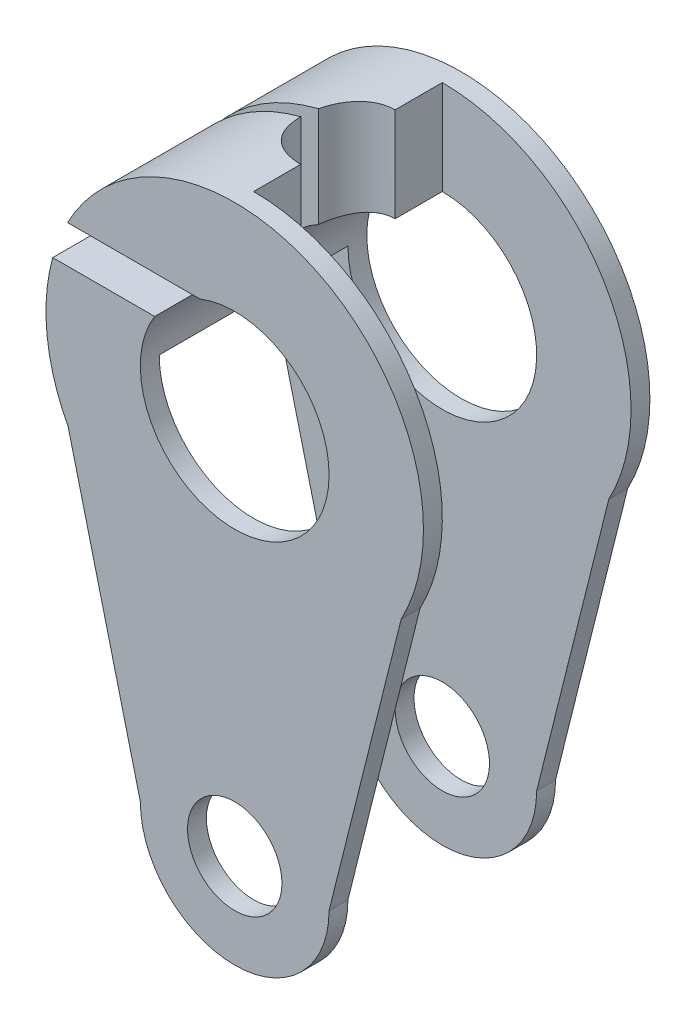
SolidWorks part; units mm, degrees
material "AISI 1020"
ref_plane "Alzado" through (0, 0, 0) normal (0, 0, 1) x (1, 0, 0)
ref_plane "Planta" through (0, 0, 0) normal (0, 1, 0) x (1, 0, 0)
ref_plane "Vista lateral" through (0, 0, 0) normal (1, 0, 0) x (0, 0, -1)
sketch "Croquis1" plane through (0, 0, 0) normal (0, 0, 1) x (1, 0, 0)
  line L0 (0, 0) -> (0, -12.7) construction
  line L1 (-5.6029, -2.9882) -> (-3.175, -12.7)
  line L2 (3.175, -12.7) -> (5.6029, -2.9882)
  arc A0 (5.6029, -2.9882) -> (-5.6029, -2.9882) centre (0, 0) ccw
  arc A1 (-3.175, -12.7) -> (3.175, -12.7) centre (0, -12.7) ccw
  circle A2 centre (0, 0) radius 3.175
  circle A3 centre (0, -12.7) radius 1.5875
  dimension "D2" = 12.7
  dimension "D3" = 6.35
  dimension "D4" = 6.35
  dimension "D5" = 3.175
  dimension "D1" = 12.7
extrude "Saliente-Extruir1" add sketch "Croquis1" along normal mid plane 7.62
sketch "Croquis2" plane through (0, 0, 0) normal (0, 1, 0) x (1, 0, 0)
  line L0 (-6.35, 3.175) -> (-6.35, -3.175)
  line L1 (-6.35, 3.81) -> (-6.35, -3.81) construction
  line L2 (-6.35, -3.175) -> (6.3565, -3.175)
  line L3 (6.3565, -3.175) -> (6.3565, 3.175)
  line L4 (-6.35, 0) -> (6.3565, 0) construction
  line L5 (-6.35, 3.175) -> (6.3565, 3.175)
  dimension "D1" = 3.175
extrude "Cortar-Extruir1" cut sketch "Croquis2" against normal blind 20.32
sketch "Croquis3" plane through (0, 0, 0) normal (1, 0, 0) x (0, 0, -1)
  line L0 (-3.175, 0) -> (-3.175, 7.62)
  line L1 (-3.175, 7.62) -> (3.175, 7.62)
  line L2 (3.175, 7.62) -> (3.175, 0)
  line L3 (3.175, 0) -> (-3.175, 0)
  dimension "D1" = 7.62
extrude "Cortar-Extruir2" cut sketch "Croquis3" along normal blind 20.32
sketch "Croquis4" plane through (0, 0, 0) normal (1, 0, 0) x (0, 0, -1)
  line L0 (-3.81, 1.6809) -> (0, 1.6809)
  line L1 (-3.81, 6.35) -> (-3.81, -2.9882) construction
  line L2 (0, 1.6809) -> (0, 2.9509)
  line L3 (0, 2.9509) -> (-3.81, 2.9509)
  line L4 (-3.81, 2.9509) -> (-3.81, 1.6809)
  dimension "D1" = 1.27
  dimension "D2" = 3.81
extrude "Cortar-Extruir3" cut sketch "Croquis4" against normal blind 20.32
sketch "Croquis5" plane through (0, 0, 0) normal (0, 1, 0) x (1, 0, 0)
  circle A0 centre (0, 0) radius 1.5875
  dimension "D1" = 3.175
extrude "Cortar-Extruir4" cut sketch "Croquis5" along normal blind 53.34
sketch "Croquis6" plane through (0, 0, 0) normal (0, 1, 0) x (1, 0, 0)
  line L0 (0, 0) -> (-5.6227, 0)
  line L1 (-5.6227, 0) -> (-6.1235, 0)
  line L2 (-6.1235, 0) -> (-6.1235, 0.508)
  line L3 (-6.1235, 0.508) -> (0, 0.508)
  line L4 (0, 0.508) -> (0, 0)
  dimension "D1" = 0.508
extrude "Cortar-Extruir6" cut sketch "Croquis6" along normal blind 53.34
